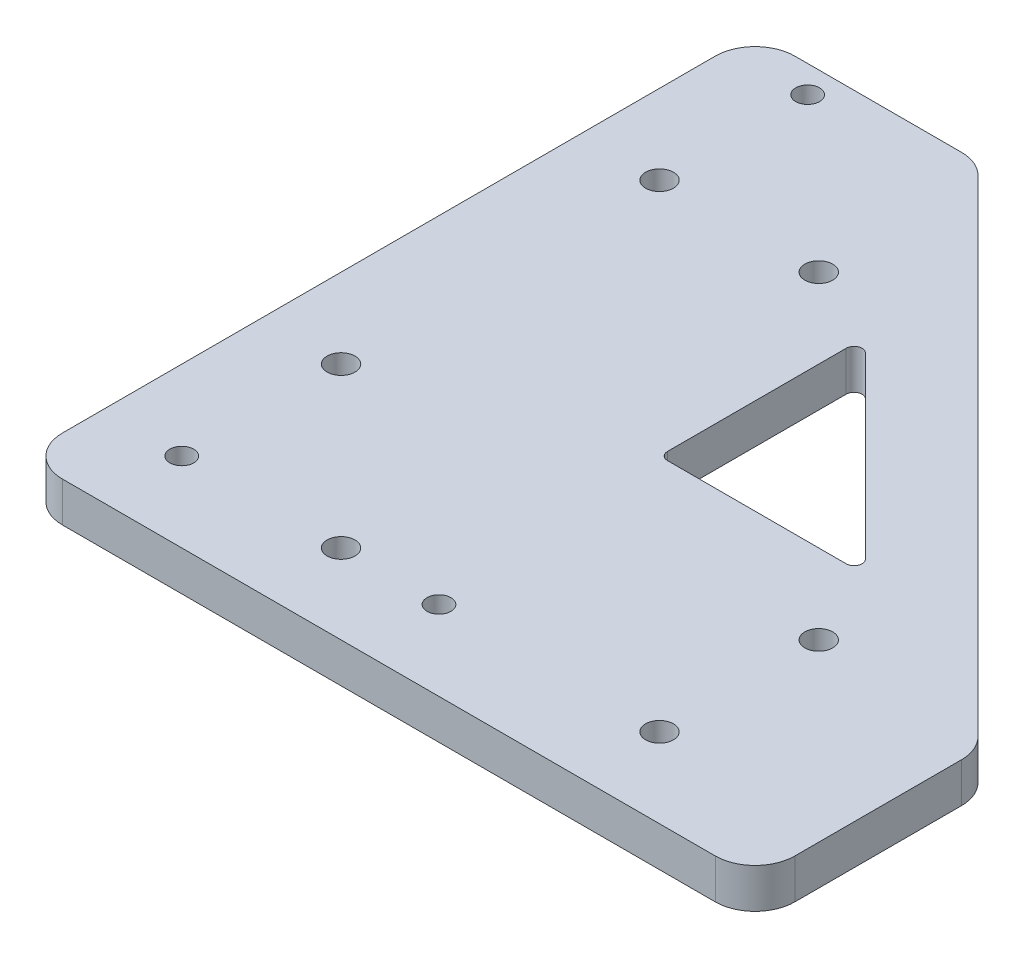
SolidWorks part; units mm, degrees
ref_plane "Plano frontal" through (0, 0, 0) normal (0, 0, 1) x (1, 0, 0)
ref_plane "Plano superior" through (0, 0, 0) normal (0, 1, 0) x (1, 0, 0)
ref_plane "Plano direito" through (0, 0, 0) normal (1, 0, 0) x (0, 0, -1)
sketch "Esboço1" plane through (0, 0, 0) normal (0, 1, 0) x (1, 0, 0)
  line L0 (0, 80) -> (0, 0)
  line L1 (0, 0) -> (80, 0)
  line L2 (80, 0) -> (80, 40)
  line L3 (80, 40) -> (40, 80)
  line L4 (40, 80) -> (0, 80)
  line L5 (40, 63.4436) -> (40, 41)
  line L6 (41, 40) -> (63.4436, 40)
  line L7 (64.1508, 41.7071) -> (41.7071, 64.1508)
  line L8 (10, 70) -> (30, 70) construction
  line L9 (70, 30) -> (70, 10) construction
  line L10 (10, 70) -> (10, 30) construction
  line L11 (30, 10) -> (70, 10) construction
  circle A0 centre (10, 70) radius 1.75
  circle A1 centre (30, 70) radius 1.75
  circle A2 centre (10, 30) radius 1.75
  circle A3 centre (70, 30) radius 1.75
  circle A4 centre (30, 10) radius 1.75
  circle A5 centre (70, 10) radius 1.75
  arc A6 (63.4436, 40) -> (64.1508, 41.7071) centre (63.4436, 41) ccw
  arc A7 (40, 41) -> (41, 40) centre (41, 41) ccw
  arc A8 (40, 63.4436) -> (41.7071, 64.1508) centre (41, 63.4436) cw
  point P26 (20, 80)
  dimension "D1" = 1
  dimension "D16" = 3.5
  dimension "D2" = 80
  dimension "D3" = 80
  dimension "D4" = 40
  dimension "D5" = 40
  dimension "D6" = 20
  dimension "D7" = 20
  dimension "D8" = 40
  dimension "D9" = 10
  dimension "D10" = 10
  dimension "D11" = 10
  dimension "D12" = 10
  dimension "D13" = 10
  dimension "D14" = 40
  dimension "D15" = 40
extrude "Ressalto-extrusão1" add sketch "Esboço1" along normal blind 5
sketch "Esboço2" plane through (0, 5, 0) normal (0, 1, 0) x (1, 0, 0)
  line L0 (40, 80) -> (0, 80) construction
  line L1 (7.175, 80) -> (12.825, 80)
  line L2 (7.175, 80) -> (7.175, 45)
  line L3 (7.175, 45) -> (12.825, 45)
  line L4 (12.825, 80) -> (12.825, 45)
  line L5 (80, 0) -> (80, 40) construction
  line L6 (27.175, 80) -> (32.825, 80)
  line L7 (27.175, 80) -> (27.175, 45)
  line L8 (27.175, 45) -> (32.825, 45)
  line L9 (32.825, 80) -> (32.825, 45)
  line L10 (80, 32.825) -> (45, 32.825)
  line L11 (80, 32.825) -> (80, 27.175)
  line L12 (80, 27.175) -> (45, 27.175)
  line L13 (45, 32.825) -> (45, 27.175)
  line L14 (10, 80) -> (10, 70) construction
  line L15 (80, 12.825) -> (45, 12.825)
  line L16 (80, 12.825) -> (80, 7.175)
  line L17 (80, 7.175) -> (45, 7.175)
  line L18 (45, 12.825) -> (45, 7.175)
  line L19 (30, 70) -> (30, 80) construction
  line L20 (80, 30) -> (70, 30) construction
  line L21 (80, 10) -> (70, 10) construction
  circle M23 centre (10, 70) radius 1.75
  line M24 (40, 80) -> (0, 80)
  line M27 (80, 0) -> (80, 40)
  circle M29 centre (30, 70) radius 1.75
  circle M30 centre (70, 30) radius 1.75
  circle M31 centre (70, 10) radius 1.75
  dimension "D1" = 5.65
  dimension "D2" = 35
extrude "Ressalto-extrusão2" [suppressed] add sketch "Esboço2" along normal blind 1 contours L4 L2 L3 M24 M23 | L9 L7 L8 M24 M29 | L10 L13 L12 M27 M30 | L15 L18 L17 M27 M31
sketch "Esboço5" plane through (0, 0, 0) normal (0, -1, 0) x (1, 0, 0)
  line L0 (80, 0) -> (92, 0)
  line L1 (92, 0) -> (92, -28)
  line L2 (92, -28) -> (80, -40)
  line L3 (80, -40) -> (80, 0)
  line L4 (80, -40) -> (40, -80) construction
  line L5 (40, -80) -> (28, -92)
  line L6 (28, -92) -> (0, -92)
  line L7 (0, -92) -> (0, -80)
  line L8 (40, -80) -> (0, -80)
  dimension "D1" = 12
  dimension "D2" = 12
extrude "Ressalto-extrusão3" add sketch "Esboço5" against normal up to surface (5 mm away) up to face at (30, 5, -8.25)
sketch "Esboço3" plane through (0, 0, 0) normal (0, -1, 0) x (1, 0, 0)
  line L0 (-8.85, -79.3) -> (-8.85, -19.3) construction
  line L1 (-8.85, -79.3) -> (61.15, -79.3) construction
  line L2 (61.15, -79.3) -> (61.15, -19.3) construction
  line L3 (-8.85, -19.3) -> (61.15, -19.3) construction
  line L4 (-8.85, -79.3) -> (61.15, -19.3) construction
  line L5 (61.15, -79.3) -> (-8.85, -19.3) construction
  line L6 (10, -10) -> (10, -88.6) construction
  line L7 (10, -10) -> (42.3, -10) construction
  line L8 (42.3, -10) -> (42.3, -88.6) construction
  line L9 (10, -88.6) -> (42.3, -88.6) construction
  line L10 (10, -10) -> (42.3, -88.6) construction
  line L11 (42.3, -10) -> (10, -88.6) construction
  line L12 (71.75, -10) -> (0, -10) construction
  line L13 (0, -92) -> (0, 0) construction
  line L14 (10, -71.75) -> (10, 0) construction
  line L15 (0, 0) -> (92, 0) construction
  circle A0 centre (10, -88.6) radius 1.5
  circle A1 centre (42.3, -88.6) radius 1.5 construction
  circle A2 centre (42.3, -10) radius 1.5
  circle A3 centre (10, -10) radius 1.5
  circle A4 centre (70, -10) radius 1.75 construction
  circle A5 centre (10, -70) radius 1.75 construction
  point P0 (26.15, -49.3)
  point P5 (26.15, -49.3)
  dimension "D3" = 3
  dimension "D1" = 70
  dimension "D2" = 60
  dimension "D4" = 78.6
  dimension "D5" = 32.3
extrude "Corte-extrusão1" cut sketch "Esboço3" against normal through all both and the other way through all contours A2 | A0 | A3
fillet "Filete1" radius 5 5 edges at (28, 2.5, -92) (0, 2.5, -92) (0, 2.5, 0) (92, 2.5, -28) (92, 2.5, 0)
